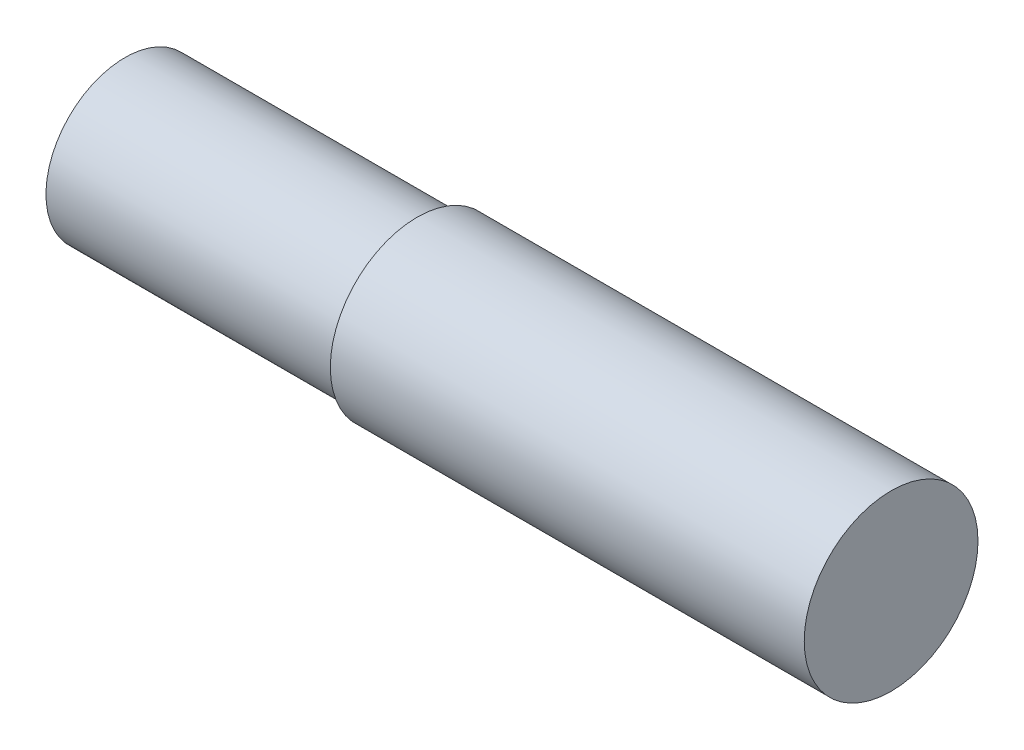
SolidWorks part; units mm, degrees
ref_plane "Plan de face" through (0, 0, 0) normal (0, 0, 1) x (1, 0, 0)
ref_plane "Plan de dessus" through (0, 0, 0) normal (0, 1, 0) x (1, 0, 0)
ref_plane "Plan de droite" through (0, 0, 0) normal (1, 0, 0) x (0, 0, -1)
sketch "Esquisse1" plane through (0, 0, 0) normal (0, 0, 1) x (1, 0, 0)
  line L0 (0, 0) -> (-48.5, 0)
  line L1 (-48.5, 0) -> (-48.5, -2.5)
  line L2 (-48.5, -2.5) -> (-35.5, -2.5)
  line L3 (-35.5, -2.5) -> (-35.5, -5.5)
  line L4 (-35.5, -5.5) -> (0, -5.5)
  line L5 (0, -5.5) -> (0, 0)
  dimension "D1" = 2.5
  dimension "D2" = 3
  dimension "D3" = 48.5
  dimension "D4" = 13
revolve "Révolution1" add sketch "Esquisse1" angle 360 about L4
sketch "Esquisse2" plane through (-48.5, 0, 0) normal (-1, 0, 0) x (0, 0, 1)
  circle A0 centre (0, -5.5) radius 5
  circle A1 centre (0, -5.5) radius 5.5 construction
  dimension "D1" = 10
extrude "Extrusion1" cut sketch "Esquisse2" against normal blind 18.5 flip side to cut
